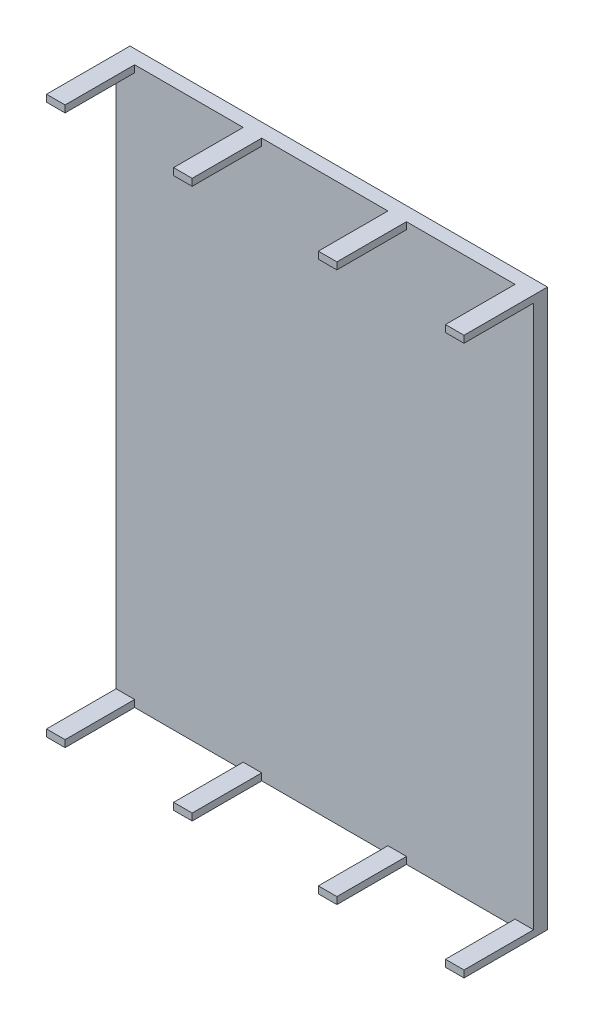
SolidWorks part; units mm, degrees
ref_plane "Front Plane" through (0, 0, 0) normal (1, 0, 0) x (0, 1, 0)
ref_plane "Top Plane" through (0, 0, 0) normal (0, 0, 1) x (0, 1, 0)
ref_plane "Right Plane" through (0, 0, 0) normal (0, 1, 0) x (-1, 0, 0)
sketch "Sketch1" plane through (0, 0, 0) normal (0, 0, 1) x (0, 1, 0)
  line L1 (0, 0) -> (-120, 0)
  line L2 (0, 0) -> (0, 90)
  line L3 (0, 90) -> (-120, 90)
  line L4 (-120, 0) -> (-120, 90)
  dimension "D1" = 90
  dimension "D2" = 120
extrude "Boss-Extrude1" add sketch "Sketch1" along normal blind 3
sketch "Sketch2" plane through (0, 0, 3) normal (0, 0, 1) x (1, 0, 0)
  line L0 (-45, 0) -> (-45, -120) construction
  line L1 (-90, 0) -> (-86, 0)
  line L2 (-90, 0) -> (-90, -1.5)
  line L3 (-90, -1.5) -> (-86, -1.5)
  line L4 (-86, 0) -> (-86, -1.5)
  line L5 (0, 0) -> (-90, 0) construction
  line L6 (-90, -120) -> (0, -120) construction
  line L7 (-90, -60) -> (0, -60) construction
  line L8 (-90, 0) -> (-90, -120) construction
  line L9 (0, -120) -> (0, 0) construction
  line L10 (0, -1.5) -> (-4, -1.5)
  line L11 (-4, 0) -> (-4, -1.5)
  line L12 (0, 0) -> (-4, 0)
  line L13 (0, 0) -> (0, -1.5)
  line L14 (0, -120) -> (0, -118.5)
  line L15 (0, -120) -> (-4, -120)
  line L16 (-4, -120) -> (-4, -118.5)
  line L17 (0, -118.5) -> (-4, -118.5)
  line L18 (-90, -118.5) -> (-86, -118.5)
  line L19 (-86, -120) -> (-86, -118.5)
  line L20 (-90, -120) -> (-86, -120)
  line L21 (-90, -120) -> (-90, -118.5)
  line L22 (-62.6, 0) -> (-58.6, 0)
  line L23 (-62.6, 0) -> (-62.6, -1.5)
  line L24 (-62.6, -1.5) -> (-58.6, -1.5)
  line L25 (-58.6, 0) -> (-58.6, -1.5)
  line L26 (-27.4, 0) -> (-27.4, -1.5)
  line L27 (-27.4, -1.5) -> (-31.4, -1.5)
  line L28 (-31.4, 0) -> (-31.4, -1.5)
  line L29 (-27.4, 0) -> (-31.4, 0)
  line L30 (-27.4, -120) -> (-31.4, -120)
  line L31 (-31.4, -120) -> (-31.4, -118.5)
  line L32 (-27.4, -118.5) -> (-31.4, -118.5)
  line L33 (-27.4, -120) -> (-27.4, -118.5)
  line L34 (-62.6, -120) -> (-62.6, -118.5)
  line L35 (-62.6, -118.5) -> (-58.6, -118.5)
  line L36 (-58.6, -120) -> (-58.6, -118.5)
  line L37 (-62.6, -120) -> (-58.6, -120)
  line M15 (0, 0) -> (-90, 0)
  line M16 (-90, 0) -> (-90, -120)
  line M17 (-90, -120) -> (0, -120)
  line M18 (0, -120) -> (0, 0)
  dimension "D1" = 1.5
  dimension "D2" = 4
  dimension "D3" = 23.4
extrude "Boss-Extrude2" add sketch "Sketch2" along normal blind 15 contours L4 L3 M15 M16 | L25 L23 L24 M15 | L28 L27 L26 M15 | L11 L10 M15 M18 | L19 L18 M17 M16 | L36 L35 L34 M17 | L32 L31 L30 L33 | L15 L16 L17 L14
